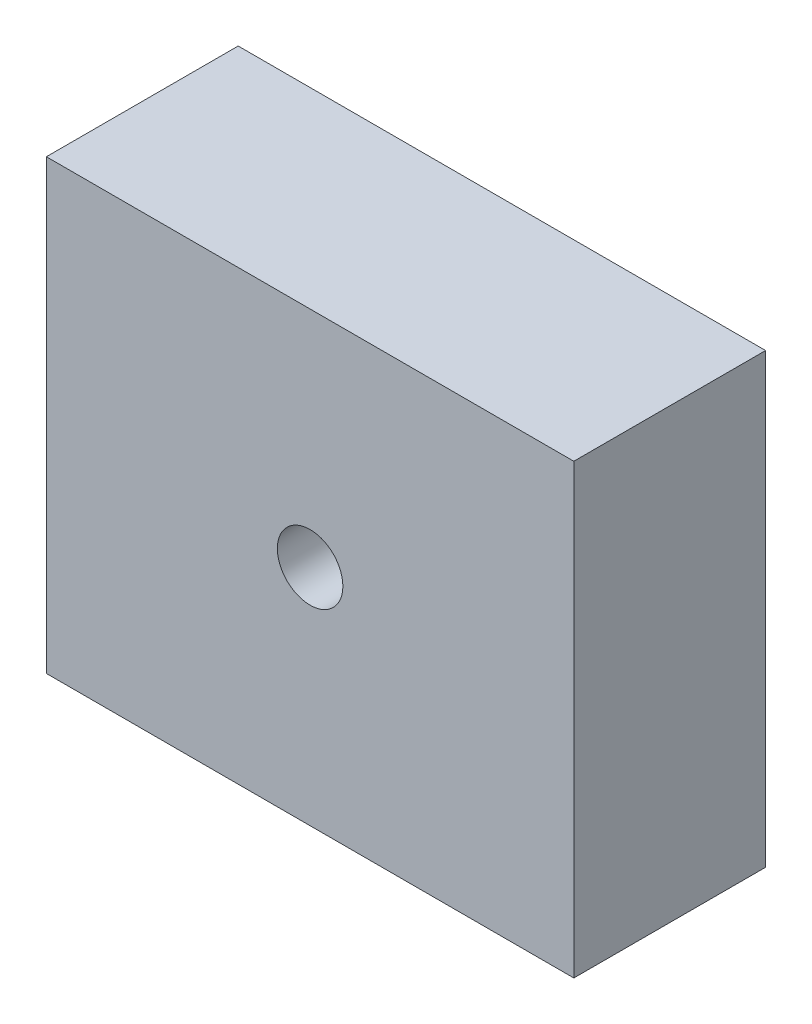
SolidWorks part; units mm, degrees
ref_plane "前视基准面" through (0, 0, 0) normal (0, 0, 1) x (1, 0, 0)
ref_plane "上视基准面" through (0, 0, 0) normal (0, 1, 0) x (1, 0, 0)
ref_plane "右视基准面" through (0, 0, 0) normal (1, 0, 0) x (0, 0, -1)
other "Configuration Table"
sketch "草图1" plane through (0, 0, 0) normal (0, 0, 1) x (1, 0, 0)
  line L0 (-33, -28) -> (33, -28)
  line L1 (33, -28) -> (33, 28)
  line L2 (33, 28) -> (-33, 28)
  line L3 (-33, 28) -> (-33, -28)
  circle A0 centre (0, 0) radius 4.1
extrude "凸台-拉伸1" add sketch "草图1" along normal blind 24
